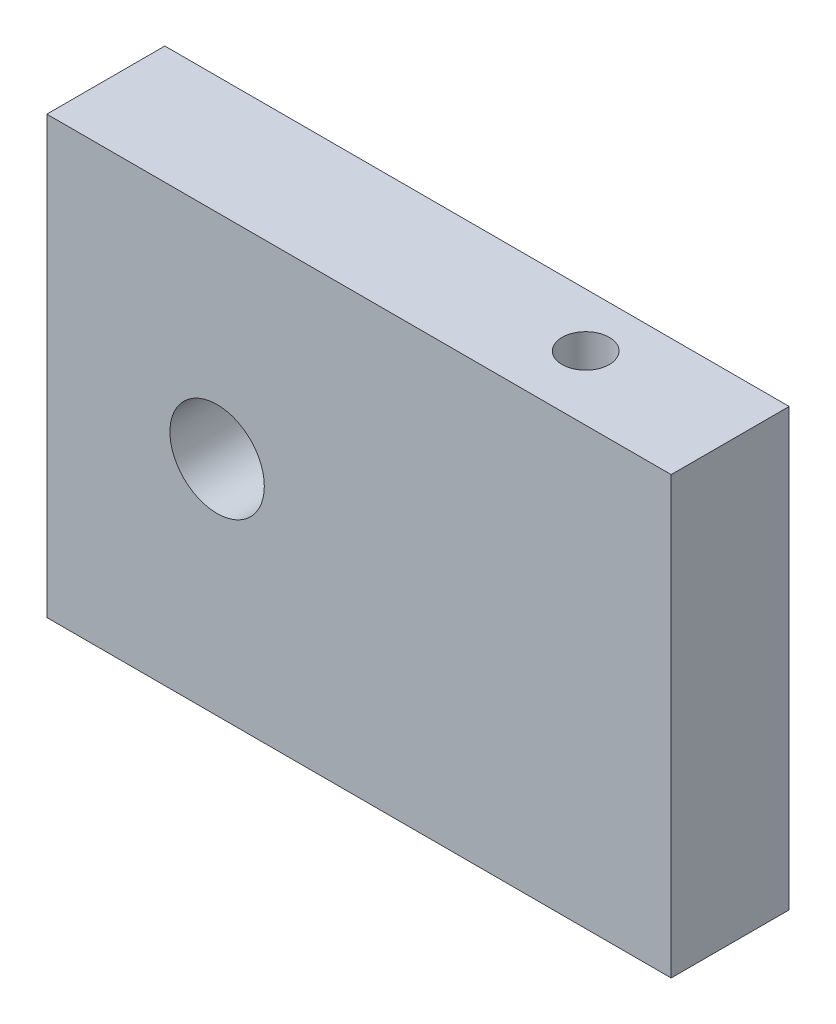
SolidWorks part; units mm, degrees
material "Brass"
ref_plane "Front Plane" through (0, 0, 0) normal (0, 0, 1) x (1, 0, 0)
ref_plane "Top Plane" through (0, 0, 0) normal (0, 1, 0) x (1, 0, 0)
ref_plane "Right Plane" through (0, 0, 0) normal (1, 0, 0) x (0, 0, -1)
sketch "Sketch1" plane through (0, 0, 0) normal (0, 0, 1) x (1, 0, 0)
  line L1 (-66.138, 46.1842) -> (66.138, 46.1842)
  line L2 (-66.138, 46.1842) -> (-66.138, -46.1842)
  line L3 (-66.138, -46.1842) -> (66.138, -46.1842)
  line L4 (66.138, 46.1842) -> (66.138, -46.1842)
  line L5 (-66.138, 46.1842) -> (66.138, -46.1842) construction
  line L6 (-66.138, -46.1842) -> (66.138, 46.1842) construction
  point P0 (0, 0)
extrude "Boss-Extrude1" add sketch "Sketch1" along normal blind 25
sketch "Sketch4" plane through (0, 0, 25) normal (0, 0, 1) x (1, 0, 0)
  point P0 (-30.06, 0.9363)
hole_wizard "Ø20.0mm Dowel Hole1" positions "Sketch4" profile "Sketch3" hole size "Ø20.0" standard "ISO" end condition through all
sketch "Sketch3" plane through (-30.06, 0.9363, 25) normal (1, 0, 0) x (0, -1, 0)
  line L0 (0, 0) -> (0, 25)
  line L1 (0, 25) -> (10, 25)
  line L2 (10, 25) -> (10, 0)
  line L5 (10, 0) -> (0, 0)
  line L11 (0, -6.35) -> (0, 107.95) construction
  dimension "Thru Hole Dia." = 20
  dimension "Thru Hole Depth" = 25
sketch "Sketch7" plane through (0, 46.1842, 0) normal (0, 1, 0) x (1, 0, 0)
  point P0 (34.3965, -11.3666)
hole_wizard "Ø10.0mm Dowel Hole1" positions "Sketch7" profile "Sketch6" hole size "Ø10.0" standard "ISO" end condition through all
sketch "Sketch6" plane through (34.3965, 46.1842, 11.3666) normal (1, 0, 0) x (0, 0, 1)
  line L0 (0, 0) -> (0, 92.3684)
  line L1 (0, 92.3684) -> (5, 92.3684)
  line L2 (5, 92.3684) -> (5, 0)
  line L5 (5, 0) -> (0, 0)
  line L11 (0, -6.35) -> (0, 107.95) construction
  dimension "Thru Hole Dia." = 10
  dimension "Thru Hole Depth" = 92.3684
